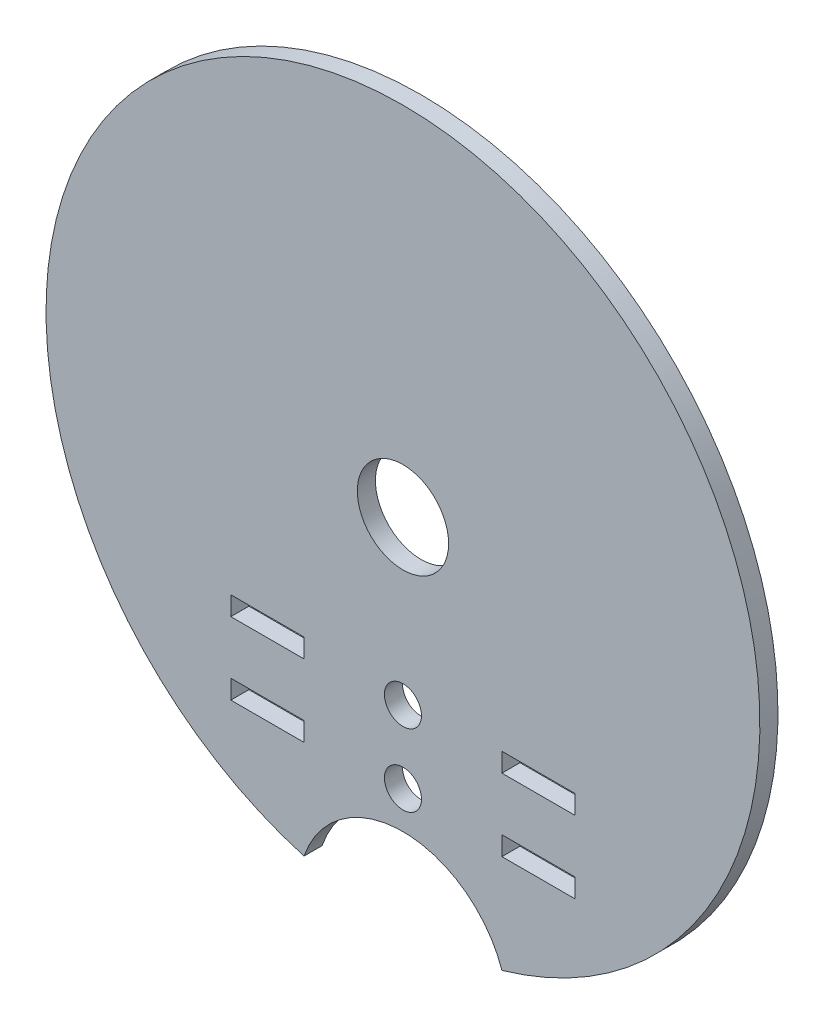
SolidWorks part; units mm, degrees
ref_plane "前视基准面" through (0, 0, 0) normal (0, 0, 1) x (1, 0, 0)
ref_plane "上视基准面" through (0, 0, 0) normal (0, 1, 0) x (1, 0, 0)
ref_plane "右视基准面" through (0, 0, 0) normal (1, 0, 0) x (0, 0, -1)
sketch "草图1" plane through (0, 0, 0) normal (0, 0, 1) x (1, 0, 0)
  line L0 (0, 0) -> (0, 8) construction
  line L1 (0, 8) -> (-15, 8) construction
  line L2 (0, 4) -> (-3.9018, 4) construction
  line L3 (-19.05, 9.05) -> (-10.95, 9.05)
  line L4 (-19.05, 9.05) -> (-19.05, 6.95)
  line L5 (-19.05, 6.95) -> (-10.95, 6.95)
  line L6 (-10.95, 9.05) -> (-10.95, 6.95)
  line L7 (-19.05, 9.05) -> (-10.95, 6.95) construction
  line L8 (-19.05, 6.95) -> (-10.95, 9.05) construction
  line L9 (-10.95, -1.05) -> (-10.95, 1.05)
  line L10 (-19.05, -1.05) -> (-10.95, -1.05)
  line L11 (-19.05, -1.05) -> (-19.05, 1.05)
  line L12 (-19.05, 1.05) -> (-10.95, 1.05)
  line L13 (10.95, 9.05) -> (10.95, 6.95)
  line L14 (19.05, 9.05) -> (10.95, 9.05)
  line L15 (19.05, 9.05) -> (19.05, 6.95)
  line L16 (19.05, 6.95) -> (10.95, 6.95)
  line L17 (19.05, 1.05) -> (10.95, 1.05)
  line L18 (19.05, -1.05) -> (19.05, 1.05)
  line L19 (19.05, -1.05) -> (10.95, -1.05)
  line L20 (10.95, -1.05) -> (10.95, 1.05)
  circle A0 centre (0, 0) radius 2.05
  circle A1 centre (0, 8) radius 2.05
  circle A2 centre (0, 26) radius 5.05
  circle A4 centre (0, 26) radius 12 construction
  circle A6 centre (0, 26) radius 39.5 construction
  arc A7 (-10.95, -11.9519) -> (10.95, -11.9519) centre (0, -15.6969) cw
  arc A8 (-10.95, -11.9519) -> (10.95, -11.9519) centre (0, 26) cw
  dimension "D1" = 4.1
  dimension "D3" = 4.1
  dimension "D7" = 10.1
  dimension "D9" = 24
  dimension "D10" = 79
  dimension "D2" = 8
  dimension "D4" = 15
  dimension "D5" = 8.1
  dimension "D6" = 2.1
  dimension "D8" = 18
extrude "凸台-拉伸1" add sketch "草图1" along normal blind 2
